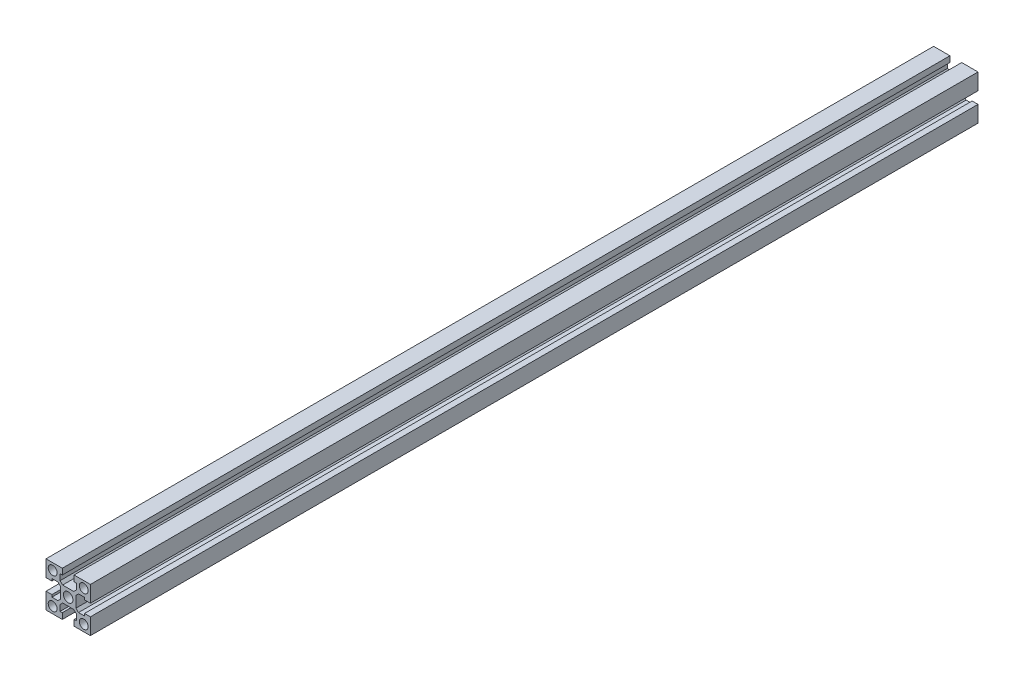
SolidWorks part; units mm, degrees
ref_plane "정면" through (0, 0, 0) normal (0, 0, 1) x (1, 0, 0)
ref_plane "윗면" through (0, 0, 0) normal (0, 1, 0) x (1, 0, 0)
ref_plane "우측면" through (0, 0, 0) normal (1, 0, 0) x (0, 0, -1)
sketch "스케치1" plane through (0, 0, 0) normal (0, 0, 1) x (1, 0, 0)
  line L0 (-10, -10) -> (-2.65, -10)
  line L1 (2.65, -10) -> (10, -10)
  line L2 (10, -10) -> (10, -2.65)
  line L3 (10, 2.65) -> (10, 10)
  line L4 (10, 10) -> (2.65, 10)
  line L5 (-2.65, 10) -> (-10, 10)
  line L6 (-10, 10) -> (-10, 2.65)
  line L7 (-10, -2.65) -> (-10, -10)
  line L8 (0, 10) -> (0, -10) construction
  line L9 (-10, 0) -> (10, 0) construction
  line L10 (2.65, 10) -> (2.65, 7.35)
  line L11 (-2.65, 10) -> (-2.65, 7.35)
  line L12 (-2.5101, 3.5) -> (0, 3.5)
  line L13 (-2.65, 7.35) -> (-3.65, 7.35)
  line L14 (-3.65, 7.35) -> (-3.65, 4.6399)
  line L15 (2.65, 7.35) -> (3.65, 7.35)
  line L16 (2.65, -10) -> (2.65, -7.35)
  line L17 (-2.65, -10) -> (-2.65, -7.35)
  line L18 (0, -3.5) -> (2.5101, -3.5)
  line L19 (-2.65, -7.35) -> (-3.65, -7.35)
  line L20 (2.65, -7.35) -> (3.65, -7.35)
  line L21 (3.65, -7.35) -> (3.65, -4.6399)
  line L22 (-10, 2.65) -> (-7.35, 2.65)
  line L23 (-10, -2.65) -> (-7.35, -2.65)
  line L24 (-3.5, 0) -> (-3.5, 2.5101)
  line L25 (-7.35, -2.65) -> (-7.35, -3.65)
  line L26 (-7.35, 2.65) -> (-7.35, 3.65)
  line L27 (-7.35, 3.65) -> (-4.6399, 3.65)
  line L28 (10, 2.65) -> (7.35, 2.65)
  line L29 (10, -2.65) -> (7.35, -2.65)
  line L30 (3.5, -2.5101) -> (3.5, 0)
  line L31 (7.35, -2.65) -> (7.35, -3.65)
  line L32 (7.35, -3.65) -> (4.6399, -3.65)
  line L33 (7.35, 2.65) -> (7.35, 3.65)
  line L34 (2.5101, -3.5) -> (3.65, -4.6399)
  line L35 (-4.6399, 3.65) -> (-3.5, 2.5101)
  line L36 (-3.65, 4.6399) -> (-2.5101, 3.5)
  line L37 (3.5, -2.5101) -> (4.6399, -3.65)
  line L38 (-2.5101, -3.5) -> (0, -3.5)
  line L39 (-2.65, -7.35) -> (-3.65, -7.35)
  line L40 (-3.65, -7.35) -> (-3.65, -4.6399)
  line L41 (0, 3.5) -> (2.5101, 3.5)
  line L42 (2.65, 7.35) -> (3.65, 7.35)
  line L43 (3.65, 7.35) -> (3.65, 4.6399)
  line L44 (-3.5, 0) -> (-3.5, -2.5101)
  line L45 (-7.35, -2.65) -> (-7.35, -3.65)
  line L46 (-7.35, -3.65) -> (-4.6399, -3.65)
  line L47 (3.5, 2.5101) -> (3.5, 0)
  line L48 (7.35, 2.65) -> (7.35, 3.65)
  line L49 (7.35, 3.65) -> (4.6399, 3.65)
  line L50 (2.5101, 3.5) -> (3.65, 4.6399)
  line L51 (-4.6399, -3.65) -> (-3.5, -2.5101)
  line L52 (-3.65, -4.6399) -> (-2.5101, -3.5)
  line L53 (3.5, 2.5101) -> (4.6399, 3.65)
  circle A0 centre (-7, 7) radius 2
  circle A1 centre (0, 0) radius 2.15
  circle A2 centre (7, 7) radius 2
  circle A3 centre (-7, -7) radius 2
  circle A4 centre (7, -7) radius 2
extrude "보스-돌출1" add sketch "스케치1" along normal mid plane 400 contours L47 L53 L49 L33 L28 L3 L4 L10 L15 L43 L50 L41 L12 L36 L14 L13 L11 L5 L6 L22 L26 L27 L35 L24 L44 L51 L46 L25 L23 L7 L0 L17 L19 L40 L52 L38 L18 L34 L21 L20 L16 L1 L2 L29 L31 L32 L37 L30 A4
